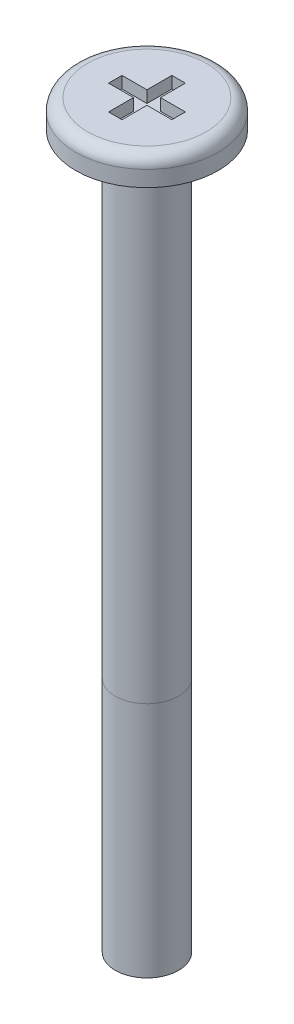
SolidWorks part; units mm, degrees
ref_plane "Front Plane" through (0, 0, 0) normal (0, 0, 1) x (1, 0, 0)
ref_plane "Top Plane" through (0, 0, 0) normal (0, 1, 0) x (1, 0, 0)
ref_plane "Right Plane" through (0, 0, 0) normal (1, 0, 0) x (0, 0, -1)
sketch "Sketch3" plane through (0, 0, 0) normal (0, 1, 0) x (1, 0, 0)
  circle A0 centre (0, 0) radius 2
  dimension "D1" = 4
extrude "Boss-Extrude1" add sketch "Sketch3" along normal blind 45
sketch "Sketch4" plane through (0, 45, 0) normal (0, 1, 0) x (1, 0, 0)
  circle A0 centre (0, 0) radius 4.5
  dimension "D1" = 9
extrude "Boss-Extrude2" add sketch "Sketch4" along normal blind 1.75
fillet "Fillet3" radius 0.75 1 edges at (0, 46.75, 4.5)
sketch "Sketch6" plane through (0, 46.75, 0) normal (0, 1, 0) x (1, 0, 0)
  line L0 (0.425, 0.425) -> (2, 0.425)
  line L1 (-2, 0.425) -> (-0.425, 0.425)
  line L2 (-2, 0.425) -> (-2, -0.425)
  line L3 (-2, -0.425) -> (-0.425, -0.425)
  line L4 (2, 0.425) -> (2, -0.425)
  line L5 (0, 0) -> (0.425, -0.0903) construction
  line L7 (-0.425, 2) -> (0.425, 2)
  line L8 (-0.425, 2) -> (-0.425, 0.425)
  line L9 (-0.425, -2) -> (0.425, -2)
  line L10 (0.425, 2) -> (0.425, 0.425)
  line L14 (-0.425, -0.425) -> (-0.425, -2)
  line L17 (0.425, -0.425) -> (0.425, -2)
  line L19 (0.425, -0.425) -> (2, -0.425)
  point P0 (0, 0)
  point P6 (0, 0)
  dimension "D1" = 4
  dimension "D2" = 4
  dimension "D3" = 0.85
  dimension "D4" = 0.85
extrude "Cut-Extrude4" cut sketch "Sketch6" against normal blind 0.75
sketch "Sketch7" plane through (0, 0, 0) normal (0, 0, 1) x (1, 0, 0)
  line L0 (-7.4335, 15) -> (10.8456, 15)
  dimension "D1" = 15
split line "Split Line1"
